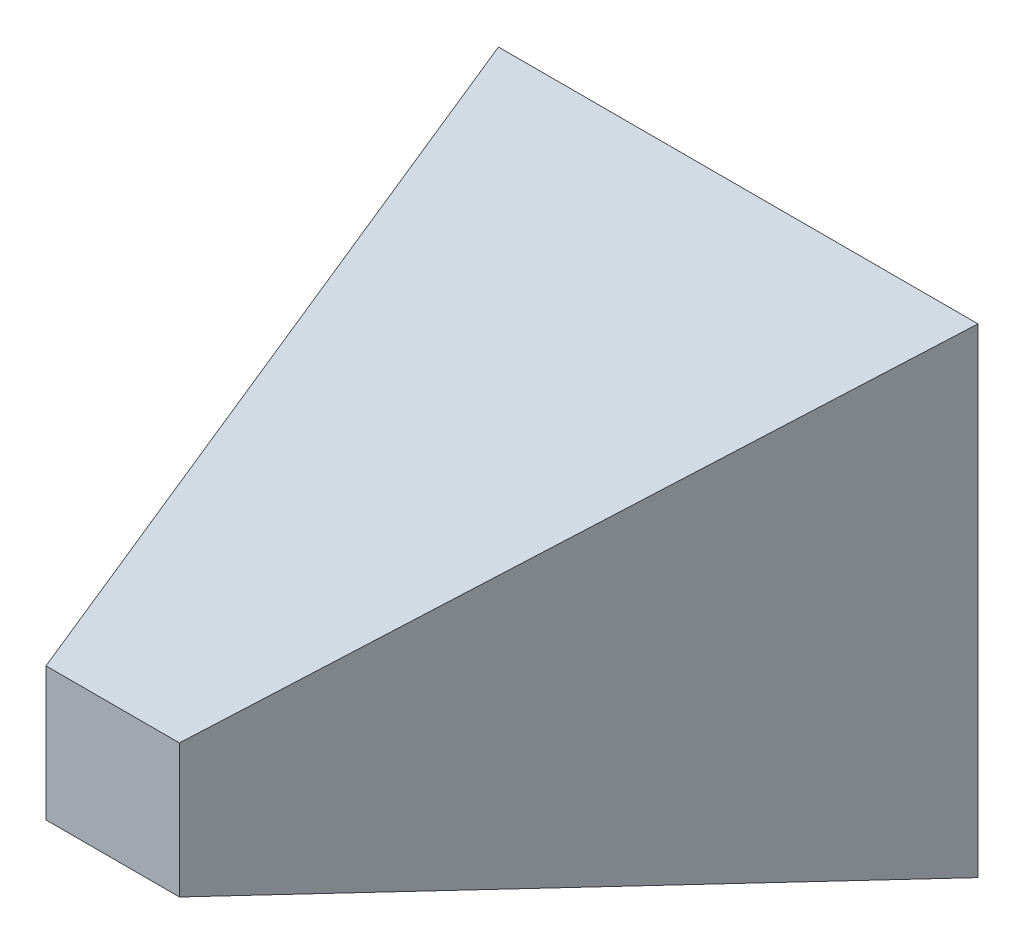
SolidWorks part; units mm, degrees
ref_plane "Front Plane" through (0, 0, 0) normal (0, 0, 1) x (1, 0, 0)
ref_plane "Top Plane" through (0, 0, 0) normal (0, 1, 0) x (1, 0, 0)
ref_plane "Right Plane" through (0, 0, 0) normal (1, 0, 0) x (0, 0, -1)
sketch "Sketch1" plane through (0, 0, 0) normal (0, 0, 1) x (1, 0, 0)
  line L1 (0, 0) -> (115, 0)
  line L2 (0, 0) -> (0, 115)
  line L3 (0, 115) -> (115, 115)
  line L4 (115, 0) -> (115, 115)
  dimension "D1" = 115
  dimension "D2" = 115
ref_plane "Plane1" through (0, 0, 150) normal (0, 0, 1) x (1, 0, 0)
sketch "Sketch2" plane through (0, 0, 150) normal (0, 0, 1) x (1, 0, 0)
  line L0 (57.5, 115) -> (57.5, 0) construction
  line L1 (41.5, 50.2216) -> (73.5, 50.2216)
  line L2 (41.5, 50.2216) -> (41.5, 82.2216)
  line L3 (41.5, 82.2216) -> (73.5, 82.2216)
  line L4 (73.5, 50.2216) -> (73.5, 82.2216)
  line L5 (0, 115) -> (115, 115) construction
  line L6 (0, 0) -> (115, 0) construction
  dimension "D1" = 32
  dimension "D2" = 32
loft "Loft1" add profiles "Sketch2", "Sketch1"
ref_plane "Plane2" through (0, 0, 100) normal (0, 0, 1) x (1, 0, 0)
ref_plane "Plane3" through (0, 0, 30) normal (0, 0, 1) x (1, 0, 0)
sketch "Sketch3" plane through (0, 0, 30) normal (0, 0, 1) x (1, 0, 0)
  line L0 (103.8366, 119.4842) -> (95.0489, 112.2109)
  line L1 (95.0489, 112.2109) -> (113.3483, 97.5761)
  line L2 (113.3483, 97.5761) -> (113.3483, 124.713)
  line L3 (113.3483, 124.713) -> (103.8366, 119.4842)
